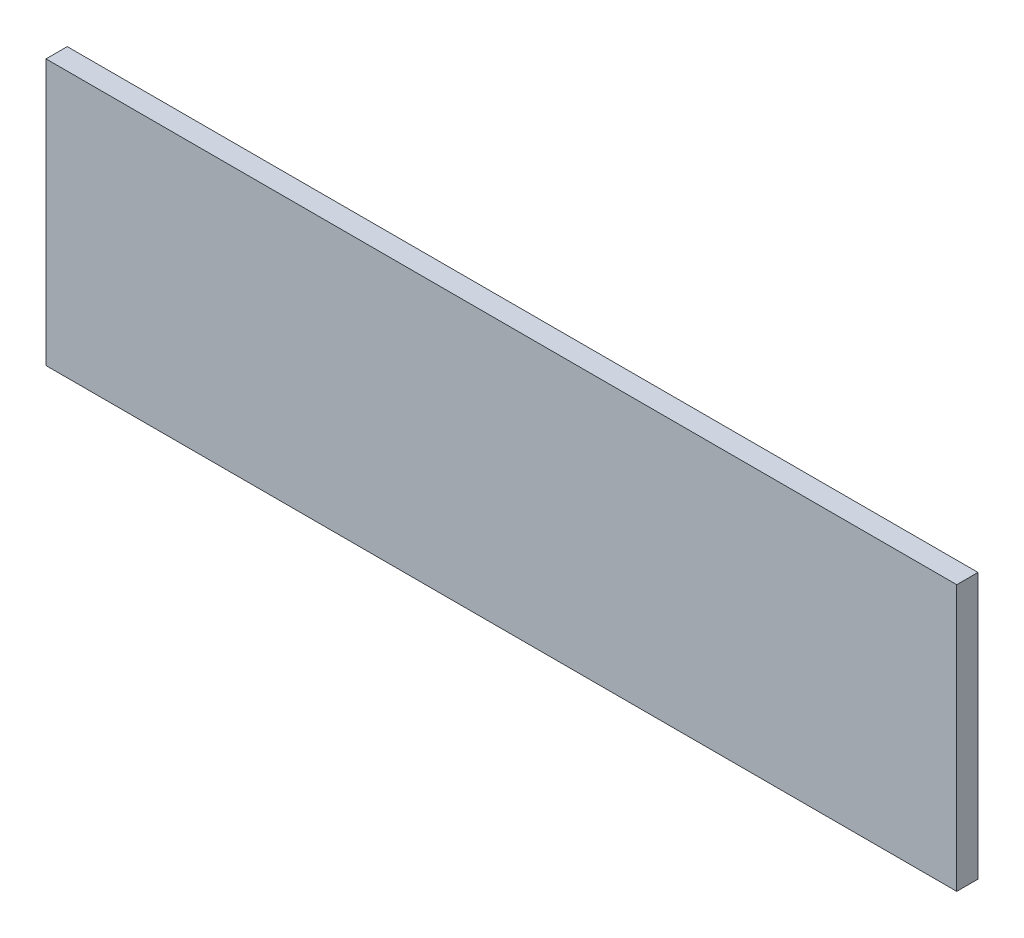
SolidWorks part; units mm, degrees
material "1060 Alloy"
ref_plane "Front Plane" through (0, 0, 0) normal (0, 0, 1) x (1, 0, 0)
ref_plane "Top Plane" through (0, 0, 0) normal (0, 1, 0) x (1, 0, 0)
ref_plane "Right Plane" through (0, 0, 0) normal (1, 0, 0) x (0, 0, -1)
sketch "Sketch1" plane through (0, 0, 0) normal (0, 0, 1) x (1, 0, 0)
  line L1 (-304.8, -88.9) -> (304.8, -88.9)
  line L2 (-304.8, -88.9) -> (-304.8, 88.9)
  line L3 (-304.8, 88.9) -> (304.8, 88.9)
  line L4 (304.8, -88.9) -> (304.8, 88.9)
  line L5 (-304.8, -88.9) -> (304.8, 88.9) construction
  line L6 (-304.8, 88.9) -> (304.8, -88.9) construction
  point P0 (0, 0)
  dimension "D1" = 609.6
  dimension "D2" = 177.8
extrude "Boss-Extrude1" add sketch "Sketch1" along normal blind 14.224
